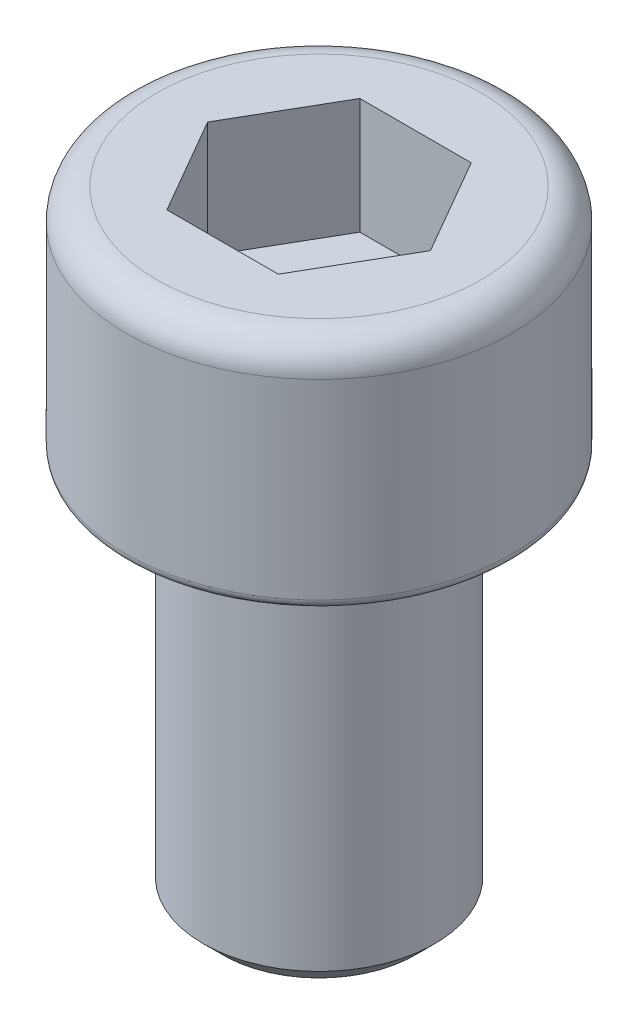
SolidWorks part; units mm, degrees
material "Plain Carbon Steel"
ref_plane "Front Plane" through (0, 0, 0) normal (0, 0, 1) x (1, 0, 0)
ref_plane "Top Plane" through (0, 0, 0) normal (0, 1, 0) x (1, 0, 0)
ref_plane "Right Plane" through (0, 0, 0) normal (1, 0, 0) x (0, 0, -1)
sketch "Sketch1" plane through (0, 0, 0) normal (0, 0, 1) x (1, 0, 0)
  line L0 (0, 0) -> (5, 0)
  line L1 (5, 0) -> (5, -6)
  line L2 (5, -6) -> (3, -6)
  line L3 (3, -6) -> (3, -16)
  line L4 (3, -16) -> (0, -16)
  line L5 (0, -16) -> (0, 0)
  line L6 (0, -21) -> (0, 5) construction
  dimension "D1" = 5
  dimension "D2" = 5
  dimension "H" = 6
  dimension "L" = 10
  dimension "D" = 6
  dimension "A" = 10
revolve "Revolve1" add sketch "Sketch1" angle 360 about L6
sketch "Sketch2" plane through (0, 0, 0) normal (0, 1, 0) x (1, 0, 0)
  line L7 (2.8868, 0) -> (1.4434, 2.5)
  line L8 (1.4434, 2.5) -> (-1.4434, 2.5)
  line L9 (-1.4434, 2.5) -> (-2.8868, 0)
  line L10 (-2.8868, 0) -> (-1.4434, -2.5)
  line L11 (-1.4434, -2.5) -> (1.4434, -2.5)
  line L12 (1.4434, -2.5) -> (2.8868, 0)
  circle A0 centre (0, 0) radius 2.5 construction
  dimension "D1" = 5
extrude "Cut-Extrude1" cut sketch "Sketch2" against normal blind 3
fillet "Fillet3" radius 0.8 1 edges at (0, 0, -5)
chamfer "Chamfer1" distance 0.5 angle 45 1 edges at (0, -16, -3)
cosmetic thread "Cosmetic Thread1" parameters "B"=7, "D2"=4.891
fillet "Fillet4" radius 0.25 2 edges at (0, -6, -3) (0, -6, -5)
